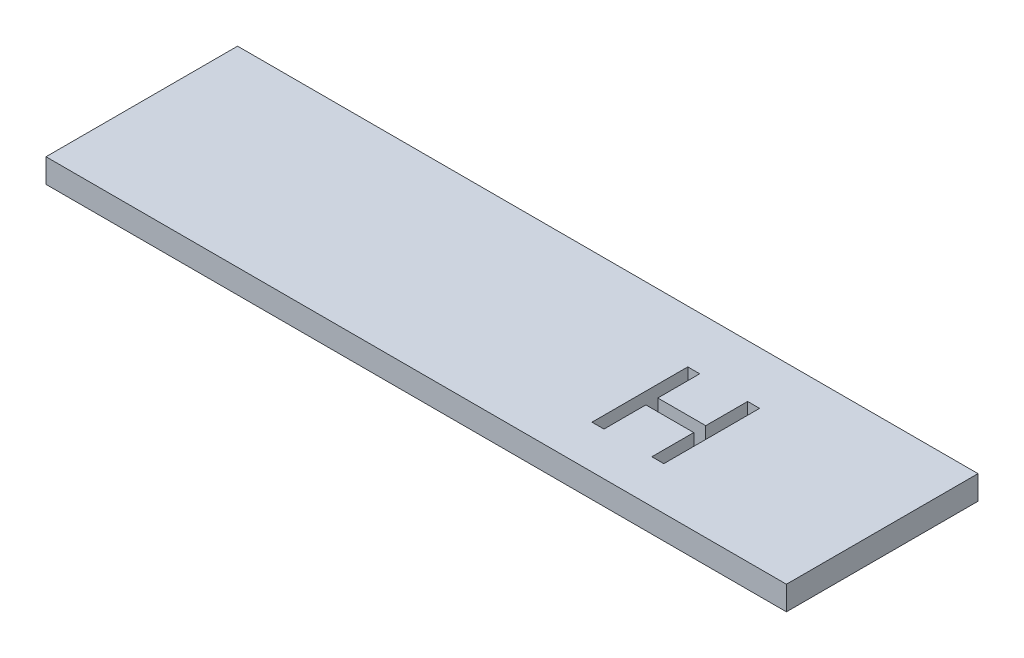
SolidWorks part; units mm, degrees
ref_plane "Front Plane" through (0, 0, 0) normal (0, 0, 1) x (1, 0, 0)
ref_plane "Top Plane" through (0, 0, 0) normal (0, 1, 0) x (1, 0, 0)
ref_plane "Right Plane" through (0, 0, 0) normal (1, 0, 0) x (0, 0, -1)
sketch "Sketch1" plane through (0, 0, 0) normal (0, 1, 0) x (1, 0, 0)
  line L1 (0, 0) -> (196.342, 0)
  line L2 (0, 0) -> (0, 50.8)
  line L3 (0, 50.8) -> (196.342, 50.8)
  line L4 (196.342, 0) -> (196.342, 50.8)
  dimension "D1" = 50.8
  dimension "D2" = 196.342
extrude "Boss-Extrude1" add sketch "Sketch1" along normal blind 6.35
sketch "Sketch2" plane through (0, 0, 0) normal (0, -1, 0) x (1, 0, 0)
  line L12 (136.525, -25.7175) -> (136.525, -36.83)
  line L13 (133.35, -11.43) -> (136.525, -11.43)
  line L14 (133.35, -11.43) -> (133.35, -36.83)
  line L15 (133.35, -36.83) -> (136.525, -36.83)
  line L16 (136.525, -11.43) -> (136.525, -22.5425)
  line L17 (149.225, -11.43) -> (152.4, -11.43)
  line L18 (149.225, -11.43) -> (149.225, -22.5425)
  line L19 (149.225, -36.83) -> (152.4, -36.83)
  line L20 (152.4, -11.43) -> (152.4, -36.83)
  line L21 (136.525, -22.5425) -> (149.225, -22.5425)
  line L23 (136.525, -25.7175) -> (149.225, -25.7175)
  line L25 (149.225, -25.7175) -> (149.225, -36.83)
  point P12 (93.742, -24.5786)
  point P13 (121.9631, -23.8794)
  point P14 (0, 0)
  point P15 (106.3015, -39.4369)
  point P16 (101.9345, -11.3999)
  dimension "D1" = 12.7
  dimension "D2" = 25.4
  dimension "D3" = 25.4
  dimension "D4" = 3.175
  dimension "D5" = 3.175
  dimension "D6" = 11.1125
  dimension "D7" = 3.175
  dimension "D8" = 133.35
  dimension "D9" = 11.43
extrude "Cut-Extrude1" cut sketch "Sketch2" against normal blind 7.62
